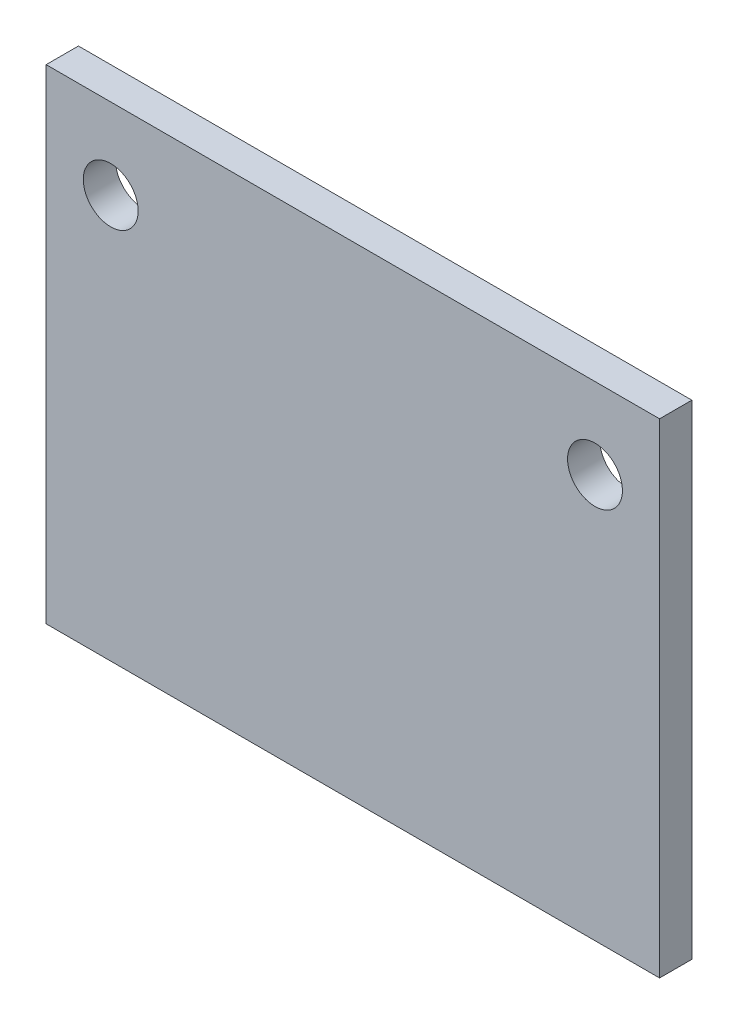
SolidWorks part; units mm, degrees
ref_plane "Front Plane" through (0, 0, 0) normal (0, 0, 1) x (1, 0, 0)
ref_plane "Top Plane" through (0, 0, 0) normal (0, 1, 0) x (1, 0, 0)
ref_plane "Right Plane" through (0, 0, 0) normal (1, 0, 0) x (0, 0, -1)
ref_plane "Plane1" through (0, 0, 2) normal (0, 0, 1) x (1, 0, 0)
sketch "Sketch1" plane through (0, 0, 2) normal (0, 0, 1) x (1, 0, 0)
  line L0 (-19, 15) -> (-19, -15)
  line L1 (-19, -15) -> (19, -15)
  line L2 (19, -15) -> (19, 15)
  line L3 (19, 15) -> (-19, 15)
  circle A0 centre (15, 9.9969) radius 1.7
  circle A1 centre (-15, 9.9969) radius 1.7
extrude "Boss-Extrude1" add sketch "Sketch1" against normal blind 2
